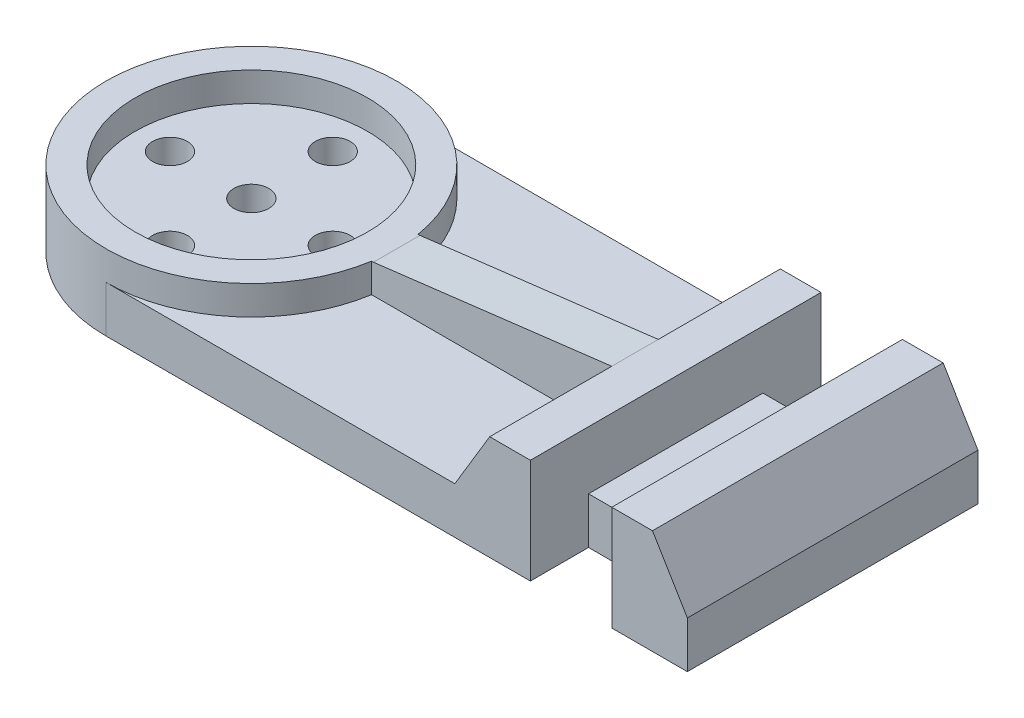
SolidWorks part; units mm, degrees
material "ABS"
ref_plane "前视基准面" through (0, 0, 0) normal (0, 0, 1) x (1, 0, 0)
ref_plane "上视基准面" through (0, 0, 0) normal (0, 1, 0) x (1, 0, 0)
ref_plane "右视基准面" through (0, 0, 0) normal (1, 0, 0) x (0, 0, -1)
sketch "草图1" plane through (0, 0, 0) normal (0, 1, 0) x (1, 0, 0)
  line L0 (0, 12.5) -> (50, 12.5)
  line L1 (0, -12.5) -> (50, -12.5)
  line L2 (50, 12.5) -> (50, -12.5)
  circle A0 centre (0, 0) radius 12.5
  dimension "D1" = 25
  dimension "D2" = 50
extrude "凸台-拉伸1" add sketch "草图1" along normal blind 4 contours A0 | A0 L1 L2 L0
sketch "草图2" plane through (0, 4, 0) normal (0, 1, 0) x (1, 0, 0)
  circle A0 centre (0, 0) radius 12.5
  circle A1 centre (0, 0) radius 10
  dimension "D1" = 25
  dimension "D2" = 20
extrude "凸台-拉伸2" add sketch "草图2" along normal blind 2.5
sketch "草图3" plane through (0, 0, 0) normal (0, -1, 0) x (1, 0, 0)
  line L0 (0, 16.9978) -> (0, -21.3221) construction
  line L1 (-30.6103, 0) -> (69.188, 0) construction
  circle A0 centre (0, 0) radius 1.5
  circle A1 centre (0, 7) radius 1.5
  circle A2 centre (7, 0) radius 1.5
  circle A3 centre (0, -7) radius 1.5
  circle A4 centre (-7, 0) radius 1.5
  circle A5 centre (40, 0) radius 1.5
  dimension "D1" = 3
  dimension "D2" = 3
  dimension "D5" = 3
  dimension "D3" = 7
  dimension "D6" = 40
  dimension "D4" = 4
extrude "切除-拉伸1" cut sketch "草图3" against normal through all
sketch "草图4" plane through (0, 0, 12.5) normal (0, 0, 1) x (1, 0, 0)
  line L0 (40, 14.1176) -> (40, -14.2645) construction
  line L2 (50, 4) -> (47, 9)
  line L3 (47, 9) -> (33, 9)
  line L4 (0, 4) -> (50, 4) construction
  line L5 (30, 4) -> (33, 9)
  line L6 (30, 4) -> (50, 4)
  point P11 (40, 9)
  dimension "D1" = 40
  dimension "D2" = 7
  dimension "D3" = 5
extrude "凸台-拉伸3" add sketch "草图4" against normal up to surface (25 mm away) up to face at (25, 2, -12.5)
sketch "草图5" plane through (0, 0, 12.5) normal (0, 0, 1) x (1, 0, 0)
  line L0 (40, 19.3346) -> (40, -11.3346) construction
  line L1 (36.5, 9) -> (43.5, 9)
  line L2 (47, 9) -> (33, 9) construction
  line L3 (43.5, 9) -> (43.5, 4)
  line L4 (43.5, 4) -> (36.5, 4)
  line L5 (36.5, 9) -> (36.5, 4)
  point P10 (40, 4)
  point P11 (40, 9)
  dimension "D1" = 40
  dimension "D2" = 3.5
  dimension "D3" = 5
extrude "切除-拉伸2" cut sketch "草图5" against normal through all
sketch "草图6" plane through (0, 4, 0) normal (0, 1, 0) x (1, 0, 0)
  line L0 (36.5, -12.5) -> (43.5, -12.5)
  line L1 (43.5, -12.5) -> (43.5, -7.5)
  line L2 (43.5, -7.5) -> (36.5, -7.5)
  line L3 (36.5, 12.5) -> (36.5, -12.5) construction
  line L4 (36.5, -7.5) -> (36.5, -12.5)
  line L5 (-16.7425, 0) -> (62.5585, 0) construction
  line L6 (36.5, 12.5) -> (43.5, 12.5)
  line L7 (36.5, 7.5) -> (36.5, 12.5)
  line L8 (43.5, 12.5) -> (43.5, 7.5)
  line L9 (43.5, 7.5) -> (36.5, 7.5)
  dimension "D1" = 5
extrude "切除-拉伸3" cut sketch "草图6" against normal through all
sketch "草图7" plane through (0, 0, 0) normal (0, 0, 1) x (1, 0, 0)
  line L4 (30, 4) -> (33, 9)
  line L5 (33, 9) -> (12.5, 6.5)
  line L9 (30, 4) -> (10.3514, 4)
  line L10 (0, 4) -> (30, 4) construction
  line L11 (10.3514, 4) -> (10.3514, 6.5)
  line L12 (12.5, 6.5) -> (-12.5, 6.5) construction
  line L13 (10.3514, 6.5) -> (12.5, 6.5)
extrude "凸台-拉伸6" add sketch "草图7" along normal mid plane 4
